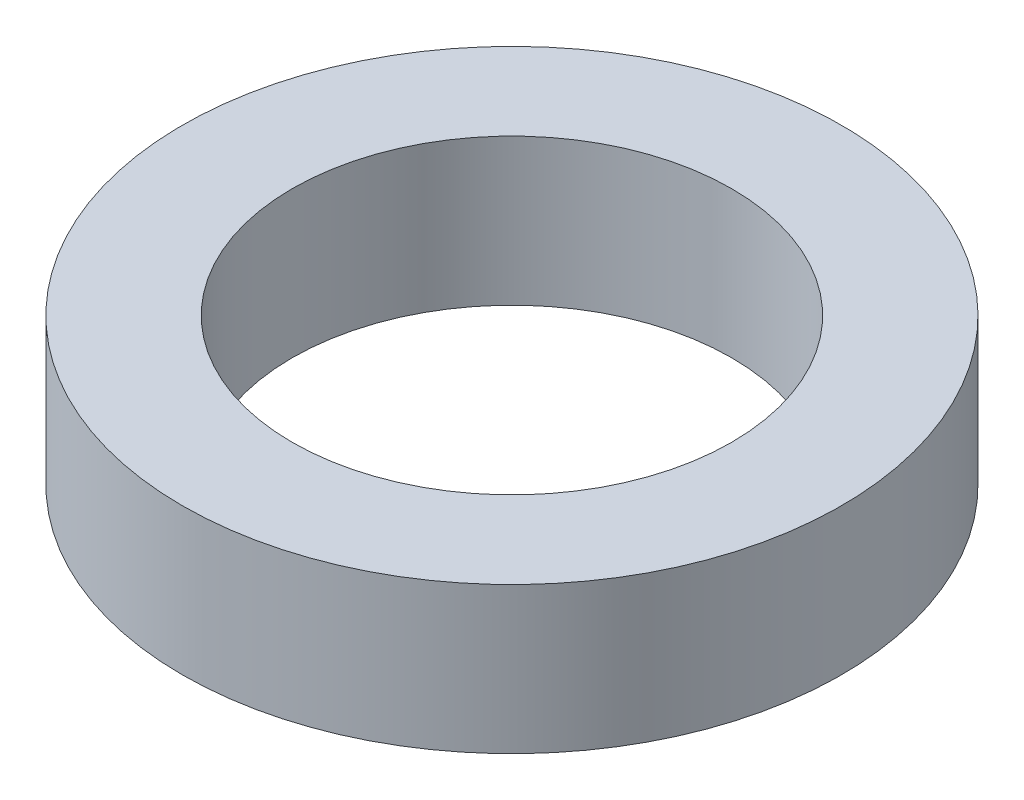
SolidWorks part; units mm, degrees
ref_plane "Front Plane" through (0, 0, 0) normal (0, 0, 1) x (1, 0, 0)
ref_plane "Top Plane" through (0, 0, 0) normal (0, 1, 0) x (1, 0, 0)
ref_plane "Right Plane" through (0, 0, 0) normal (1, 0, 0) x (0, 0, -1)
sketch "Sketch1" plane through (0, 0, 0) normal (0, 1, 0) x (1, 0, 0)
  circle A0 centre (0, 0) radius 6
  circle A1 centre (0, 0) radius 9
  dimension "D1" = 18
  dimension "D2" = 12
extrude "Boss-Extrude1" add sketch "Sketch1" along normal blind 4
